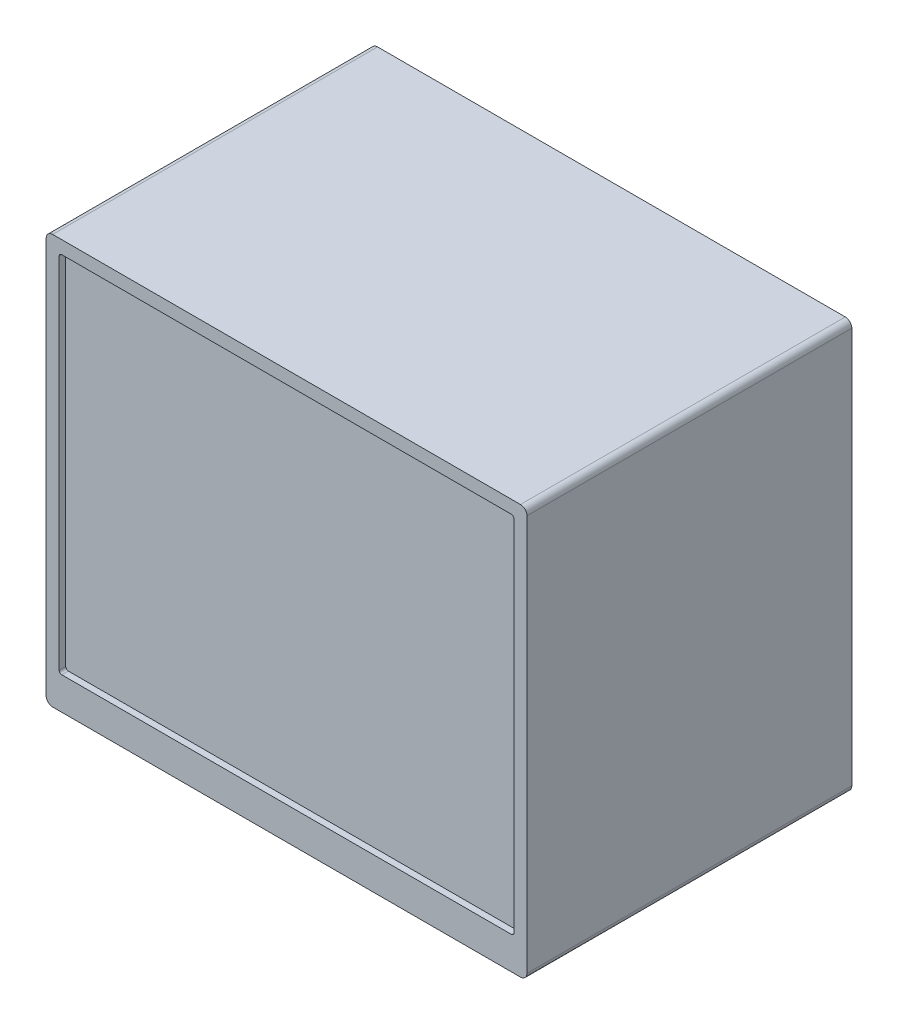
SolidWorks part; units mm, degrees
ref_plane "Front Plane" through (0, 0, 0) normal (0, 0, 1) x (1, 0, 0)
ref_plane "Top Plane" through (0, 0, 0) normal (0, 1, 0) x (1, 0, 0)
ref_plane "Right Plane" through (0, 0, 0) normal (1, 0, 0) x (0, 0, -1)
sketch "Sketch1" plane through (0, 0, 0) normal (0, 0, 1) x (1, 0, 0)
  line L1 (-177.1192, 114.7382) -> (192.8808, 114.7382)
  line L2 (-177.1192, 114.7382) -> (-177.1192, -200.2618)
  line L3 (-177.1192, -200.2618) -> (192.8808, -200.2618)
  line L4 (192.8808, 114.7382) -> (192.8808, -200.2618)
  dimension "D1" = 370
  dimension "D2" = 315
extrude "Boss-Extrude1" add sketch "Sketch1" along normal blind 250
fillet "Fillet2" radius 5 4 edges at (192.8808, -200.2618, 125) (192.8808, 114.7382, 125) (-177.1192, -200.2618, 125) (-177.1192, 114.7382, 125)
sketch "Sketch3" plane through (0, 0, 250) normal (0, 0, 1) x (1, 0, 0)
  line L0 (187.8808, 114.7382) -> (-172.1192, 114.7382) construction
  line L1 (-167.1192, 104.7382) -> (182.8808, 104.7382)
  line L2 (-167.1192, 104.7382) -> (-167.1192, -175.2618)
  line L3 (-167.1192, -175.2618) -> (182.8808, -175.2618)
  line L4 (182.8808, 104.7382) -> (182.8808, -175.2618)
  line L5 (-177.1192, 109.7382) -> (-177.1192, -195.2618) construction
  line L6 (192.8808, -195.2618) -> (192.8808, 109.7382) construction
  line L7 (-172.1192, -200.2618) -> (187.8808, -200.2618) construction
  dimension "D1" = 10
  dimension "D2" = 10
  dimension "D3" = 10
  dimension "D4" = 25
extrude "Cut-Extrude1" cut sketch "Sketch3" against normal blind 5
fillet "Fillet3" radius 2 4 edges at (182.8808, -175.2618, 247.5) (182.8808, 104.7382, 247.5) (-167.1192, 104.7382, 247.5) (-167.1192, -175.2618, 247.5)
scale "Scale3" scale about centroid uniform scaling yes scale factor 0.3
